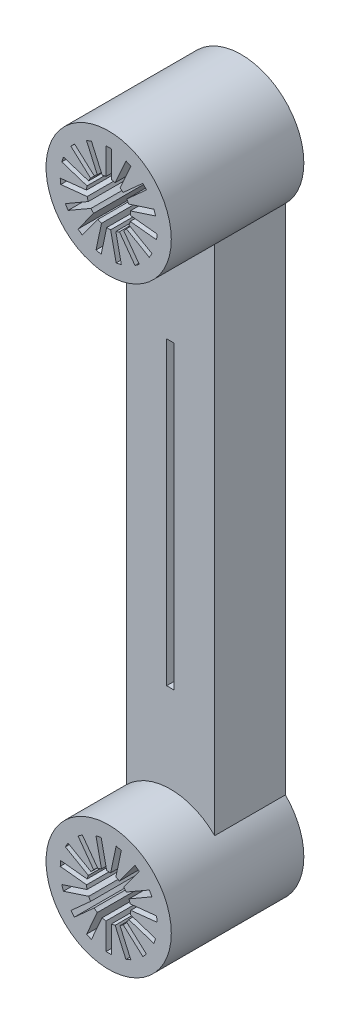
SolidWorks part; units mm, degrees
ref_plane "Front Plane" through (0, 0, 0) normal (0, 0, 1) x (1, 0, 0)
ref_plane "Top Plane" through (0, 0, 0) normal (0, 1, 0) x (1, 0, 0)
ref_plane "Right Plane" through (0, 0, 0) normal (1, 0, 0) x (0, 0, -1)
sketch "Sketch1" plane through (0, 0, 0) normal (0, 0, 1) x (1, 0, 0)
  line L1 (-6.35, -43.18) -> (6.35, -43.18)
  line L2 (-6.35, -43.18) -> (-6.35, 43.18)
  line L3 (-6.35, 43.18) -> (6.35, 43.18)
  line L4 (6.35, -43.18) -> (6.35, 43.18)
  line L5 (-6.35, -43.18) -> (6.35, 43.18) construction
  line L6 (-6.35, 43.18) -> (6.35, -43.18) construction
  point P0 (0, 0)
  dimension "D1" = 12.7
  dimension "D2" = 86.36
extrude "Boss-Extrude1" add sketch "Sketch1" along normal blind 10.16
sketch "Sketch2" plane through (0, 0, 10.16) normal (0, 0, 1) x (1, 0, 0)
  line L0 (6.35, -43.18) -> (6.35, 43.18) construction
  line L1 (-0.5588, -21.59) -> (0.508, -21.59)
  line L2 (-0.5588, -21.59) -> (-0.5588, 21.59)
  line L3 (-0.5588, 21.59) -> (0.508, 21.59)
  line L4 (0.508, -21.59) -> (0.508, 21.59)
  line L5 (-0.5588, -21.59) -> (0.508, 21.59) construction
  line L6 (-0.5588, 21.59) -> (0.508, -21.59) construction
  point P0 (0, 0)
  dimension "D1" = 43.18
  dimension "D2" = 1.0668
  dimension "D3" = 5.842
extrude "Cut-Extrude1" cut sketch "Sketch2" against normal offset from surface (5.08 mm away) 5.08 up to face at (0, 0, 0)
ref_plane "Plane1" through (0, 0, 0) normal (0, 1, 0) x (1, 0, 0)
sketch "Sketch12" plane through (0, 0, 10.16) normal (0, 0, 1) x (1, 0, 0)
  line L0 (6.35, 43.18) -> (-6.35, 43.18) construction
  circle A0 centre (0, 43.18) radius 9
  dimension "D1" = 18
extrude "Boss-Extrude3" add sketch "Sketch12" along normal blind 8.89 and the other way blind 10.16
sketch "Sketch13" plane through (0, 0, 19.05) normal (0, 0, 1) x (1, 0, 0)
  circle A0 centre (0, 43.18) radius 3.175
  dimension "D1" = 6.35
extrude "Cut-Extrude3" cut sketch "Sketch13" against normal through all
sketch "Sketch15" plane through (0, 0, 19.05) normal (0, 0, 1) x (1, 0, 0)
  line L0 (0.381, 46.3321) -> (-0.381, 46.3321)
  line L1 (0.381, 46.3321) -> (0.381, 50.1421)
  line L2 (-0.381, 46.3321) -> (-0.381, 50.1421)
  line L3 (0.381, 50.1421) -> (-0.381, 50.1421)
  circle A0 centre (0, 43.18) radius 3.175 construction
  dimension "D1" = 0.762
  dimension "D2" = 3.81
extrude "Cut-Extrude4" cut sketch "Sketch15" against normal through all
pattern_circular "CirPattern1" count 15 over 360 about axis through (0, 43.18, 0) along (0, 0, 1) of "Cut-Extrude4"
mirror "Mirror2" about plane through (0, 0, 0) normal (0, 1, 0) of "CirPattern1", "Cut-Extrude4", "Cut-Extrude3", "Boss-Extrude3"
hole_wizard "M6 Clearance Hole1" positions "Sketch17" profile "Sketch16" hole size "M6" standard "ANSI Metric"
sketch "Sketch17" plane through (0, 0, 0) normal (0, 0, -1) x (-1, 0, 0)
  point P0 (0, 0)
sketch "Sketch16" plane through (0, 0, 0) normal (1, 0, 0) x (0, 1, 0)
  line L0 (0, 0) -> (0, 2.54)
  line L1 (0, 2.54) -> (3.5, 2.54)
  line L2 (3.5, 2.54) -> (3.5, 0)
  line L5 (3.5, 0) -> (0, 0)
  line L10 (0, 2.54) -> (-3.5, 2.54) construction
  line L11 (0, -6.35) -> (0, 107.95) construction
  dimension "Hole Dia." = 7
  dimension "Hole Depth" = 2.54
  dimension "Drill Angle" = 180
